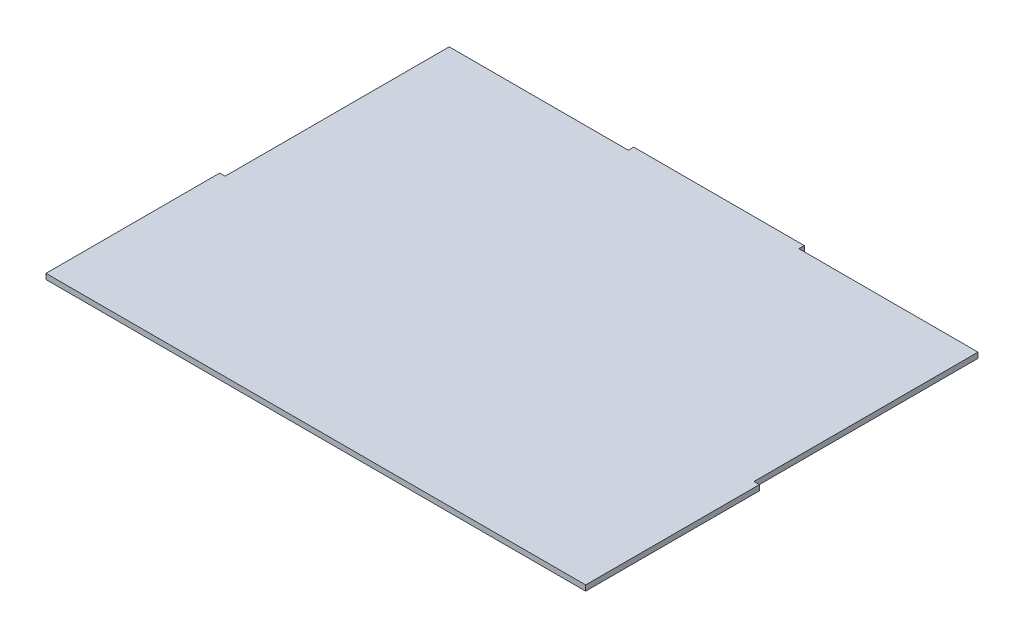
SolidWorks part; units mm, degrees
material "6061-T6 (SS)"
ref_plane "X-Y Datum" through (0, 0, 0) normal (0, 0, 1) x (1, 0, 0)
ref_plane "X-Z Datum" through (0, 0, 0) normal (0, 1, 0) x (1, 0, 0)
ref_plane "Y-Z Datum" through (0, 0, 0) normal (1, 0, 0) x (0, 0, -1)
sketch "Sketch1" plane through (0, 0, 0) normal (0, 0, 1) x (1, 0, 0)
  line L1 (-157.79, -1.5875) -> (157.79, -1.5875)
  line L2 (-157.79, -1.5875) -> (-157.79, 1.5875)
  line L3 (-157.79, 1.5875) -> (157.79, 1.5875)
  line L4 (157.79, -1.5875) -> (157.79, 1.5875)
  line L5 (-157.79, -1.5875) -> (157.79, 1.5875) construction
  line L6 (-157.79, 1.5875) -> (157.79, -1.5875) construction
  point P0 (0, 0)
  dimension "D1" = 315.58
  dimension "D2" = 3.175
extrude "Boss-Extrude1" add sketch "Sketch1" along normal blind 232.6
sketch "Sketch5" plane through (0, 1.5875, 0) normal (0, 1, 0) x (1, 0, 0)
  line L15 (-157.79, 0) -> (-154.615, 0)
  line L16 (-157.79, 0) -> (-157.79, -131)
  line L17 (-157.79, -131) -> (-154.615, -131)
  line L18 (-154.615, 0) -> (-154.615, -131)
  dimension "D3" = 3.175
  dimension "D4" = 131
extrude "Cut-Extrude2" cut sketch "Sketch5" against normal through all and the other way through all
mirror "Mirror1" about plane through (0, 0, 0) normal (1, 0, 0) of "Cut-Extrude2"
sketch "Sketch7" plane through (0, -1.5875, 0) normal (0, -1, 0) x (1, 0, 0)
  line L0 (110.4954, 221.3083) -> (104.4954, 221.3083) construction
  circle A0 centre (107.4954, 221.3083) radius 3.302
  dimension "D1" = 6.604
extrude "Cut-Extrude3" [suppressed] cut sketch "Sketch7" against normal through all
pattern_linear "LPattern1" [suppressed] count 3 spacing 101.6
sketch "Sketch10" plane through (0, 0, 0) normal (0, 0, -1) x (-1, 0, 0)
  line L0 (-154.615, -1.5875) -> (-154.615, 1.5875) construction
  line L2 (154.615, -1.5875) -> (154.615, 1.5875) construction
  line L4 (-154.615, 1.5875) -> (154.615, 1.5875) construction
  line L5 (-49.84, 1.5875) -> (49.84, 1.5875)
  line L6 (-49.84, 1.5875) -> (-49.84, -1.5875)
  line L7 (-49.84, -1.5875) -> (49.84, -1.5875)
  line L8 (49.84, 1.5875) -> (49.84, -1.5875)
  line L9 (154.615, -1.5875) -> (-154.615, -1.5875) construction
  dimension "D1" = 104.775
  dimension "D2" = 104.775
extrude "Boss-Extrude2" add sketch "Sketch10" along normal blind 3.175
